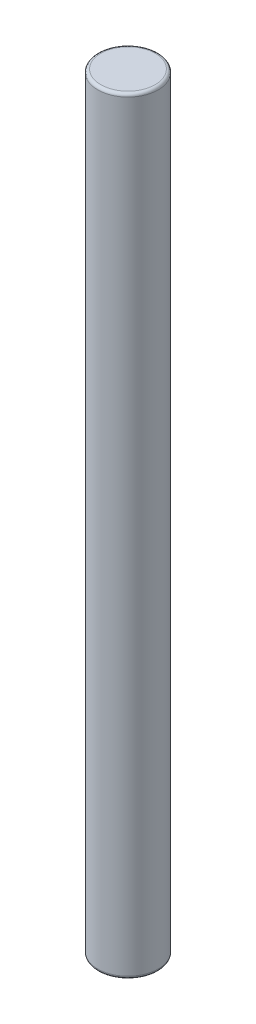
SolidWorks part; units mm, degrees
ref_plane "Front Plane" through (0, 0, 0) normal (0, 0, 1) x (1, 0, 0)
ref_plane "Top Plane" through (0, 0, 0) normal (0, 1, 0) x (1, 0, 0)
ref_plane "Right Plane" through (0, 0, 0) normal (1, 0, 0) x (0, 0, -1)
sketch "Sketch1" plane through (0, 0, 0) normal (0, 1, 0) x (1, 0, 0)
  circle A0 centre (0, 0) radius 5
  dimension "D1" = 10
extrude "Boss-Extrude1" add sketch "Sketch1" along normal blind 127
fillet "Fillet1" radius 0.5 2 edges at (0, 0, 5) (0, 127, 5)
